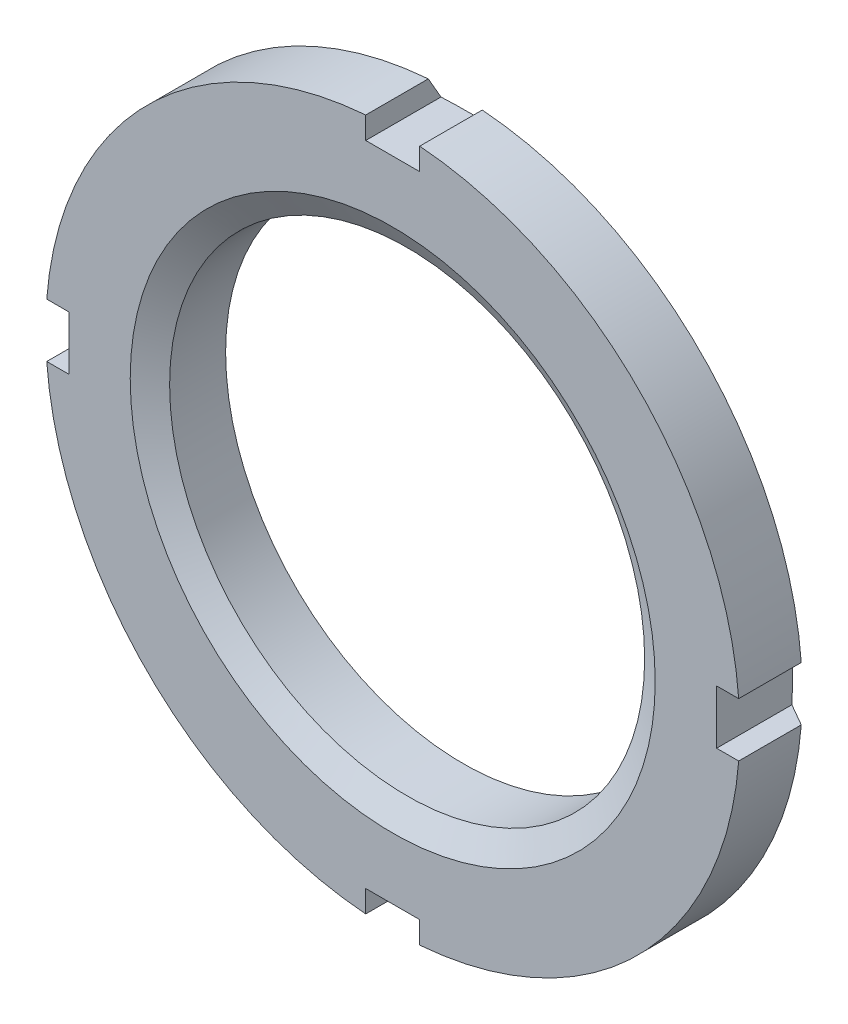
SolidWorks part; units mm, degrees
ref_plane "Přední rovina" through (0, 0, 0) normal (0, 0, 1) x (1, 0, 0)
ref_plane "Vrchní rovina" through (0, 0, 0) normal (0, 1, 0) x (1, 0, 0)
ref_plane "Pravá rovina" through (0, 0, 0) normal (1, 0, 0) x (0, 0, -1)
sketch "Skica1" plane through (0, 0, 0) normal (0, 0, 1) x (1, 0, 0)
  circle A0 centre (0, 0) radius 90
  circle A1 centre (0, 0) radius 61.6
  dimension "D1" = 123.2
  dimension "D2" = 180
extrude "Vysunout1" add sketch "Skica1" along normal mid plane 22
cosmetic thread "Kosmetický závit1" parameters "D2"=140
chamfer "Zkosit2" distance 3.74 angle 60 1 edges at (61.6, 0, -11)
chamfer "Zkosit3" distance 3.74 angle 60 1 edges at (61.6, 0, 11)
sketch "Skica4" plane through (0, 0, 0) normal (0, 1, 0) x (1, 0, 0)
  line L0 (90, 11) -> (80, 11)
  line L1 (90, 11) -> (-90, 11) construction
  line L2 (80, 11) -> (90, 5.2265)
  line L3 (90, -11) -> (90, 11) construction
  line L4 (90, 5.2265) -> (90, 11)
  line L5 (0, 0) -> (0, 11) construction
  line L6 (68.0779, 11) -> (-68.0779, 11) construction
  dimension "D1" = 160
  dimension "D2" = 30
revolve "Odebrat otočením1" cut sketch "Skica4" angle 360 about L5
sketch "Skica2" plane through (0, 0, 11) normal (0, 0, 1) x (1, 0, 0)
  line L0 (0, 0) -> (0, 84) construction
  line L1 (-7, 90) -> (7, 90)
  line L2 (-7, 90) -> (-7, 84)
  line L3 (-7, 84) -> (7, 84)
  line L4 (7, 90) -> (7, 84)
  circle A1 centre (0, 0) radius 90 construction
  dimension "D1" = 6
  dimension "D2" = 14
extrude "Odebrat vysunutím1" cut sketch "Skica2" against normal up to next
pattern_circular "Kruhové pole1" count 4 over 360 about axis through (0, 0, 0) along (0, 0, 1) of "Odebrat vysunutím1"
equation "\"D1@Zkosit2\" = \"D1@Vysunout1\"*0.17"
equation "\"D1@Zkosit3\" =\"D1@Vysunout1\"*0.17"
equation "\"D1@Skica1\" = \"D2@Kosmetický závit1\"*0.88"
